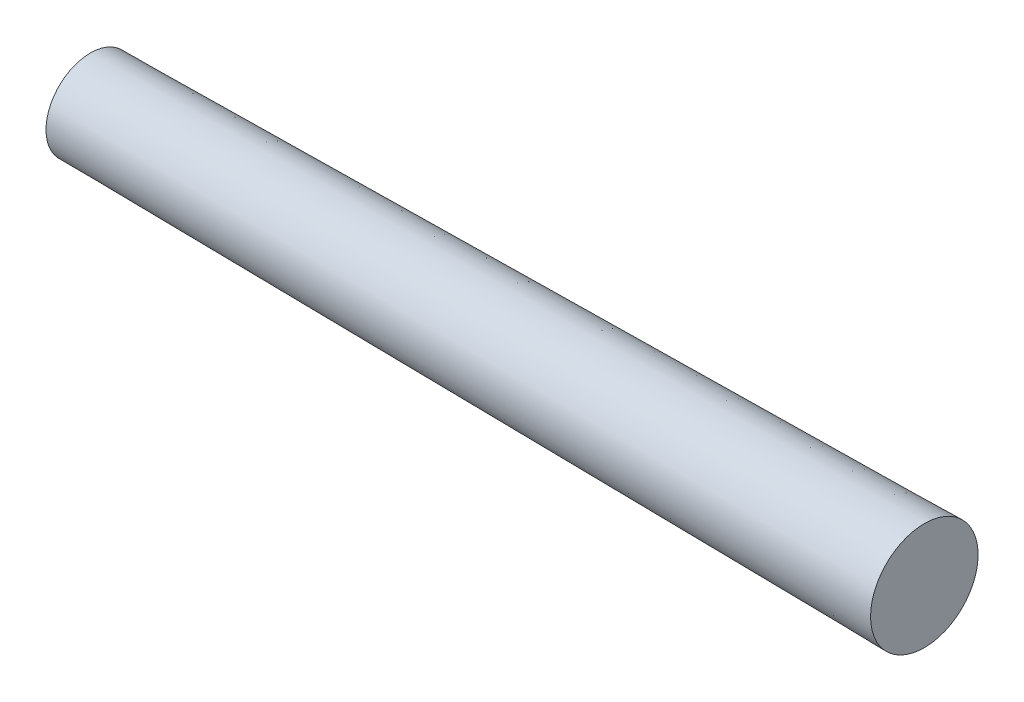
SolidWorks part; units mm, degrees
ref_plane "Front Plane" through (0, 0, 0) normal (0, 0, 1) x (1, 0, 0)
ref_plane "Top Plane" through (0, 0, 0) normal (0, 1, 0) x (1, 0, 0)
ref_plane "Right Plane" through (0, 0, 0) normal (1, 0, 0) x (0, 0, -1)
sketch "Sketch1" plane through (0, 0, 0) normal (0, 0, 1) x (1, 0, 0)
  line L0 (-6.35, 0) -> (6.35, 0) construction
  line L1 (-6.2179, 0.6604) -> (6.19, 0.8001)
  line L2 (6.35, 0) -> (6.35, 0.8019) construction
  line L3 (-6.35, 0) -> (-6.35, 0.6589) construction
  line L4 (-6.35, 0) -> (6.35, 0)
  line L5 (-6.2179, 0.6604) -> (-6.2179, -0.6604) construction
  line L6 (6.19, 0.8001) -> (6.19, -0.8001) construction
  arc A0 (6.35, 0) -> (6.19, 0.8001) centre (4.2697, 0) ccw
  arc A1 (-6.35, 0) -> (-6.2179, 0.6604) centre (-4.633, 0) cw
  dimension "D1" = 0.1321
  dimension "Length" = 12.7
  dimension "D2" = 0.16
  dimension "D3" = 1.6002
  dimension "Small End Dia." = 1.3208
  dimension "D4" = 1.3208
  dimension "Large End Dia" = 1.6002
revolve "Revolve1" add sketch "Sketch1" angle 360 about L4
sketch "Sketch2" plane through (0, 0, 0) normal (0, 0, 1) x (1, 0, 0)
  line L1 (6.19, -0.8001) -> (6.6839, -0.8001)
  line L2 (6.19, -0.8001) -> (6.19, 0.8001)
  line L3 (6.19, 0.8001) -> (6.6839, 0.8001)
  line L4 (6.6839, -0.8001) -> (6.6839, 0.8001)
extrude "Cut-Extrude1" cut sketch "Sketch2" against normal through all and the other way through all
equation "\"D1@Sketch1\" = \"Small End Dia.@Sketch1\"*.1"
equation "\"D2@Sketch1\" = \"Large End Dia@Sketch1\"*.1"
equation "\"D3@Sketch1\" = \"Large End Dia@Sketch1\""
equation "\"D4@Sketch1\" = \"Small End Dia.@Sketch1\""
